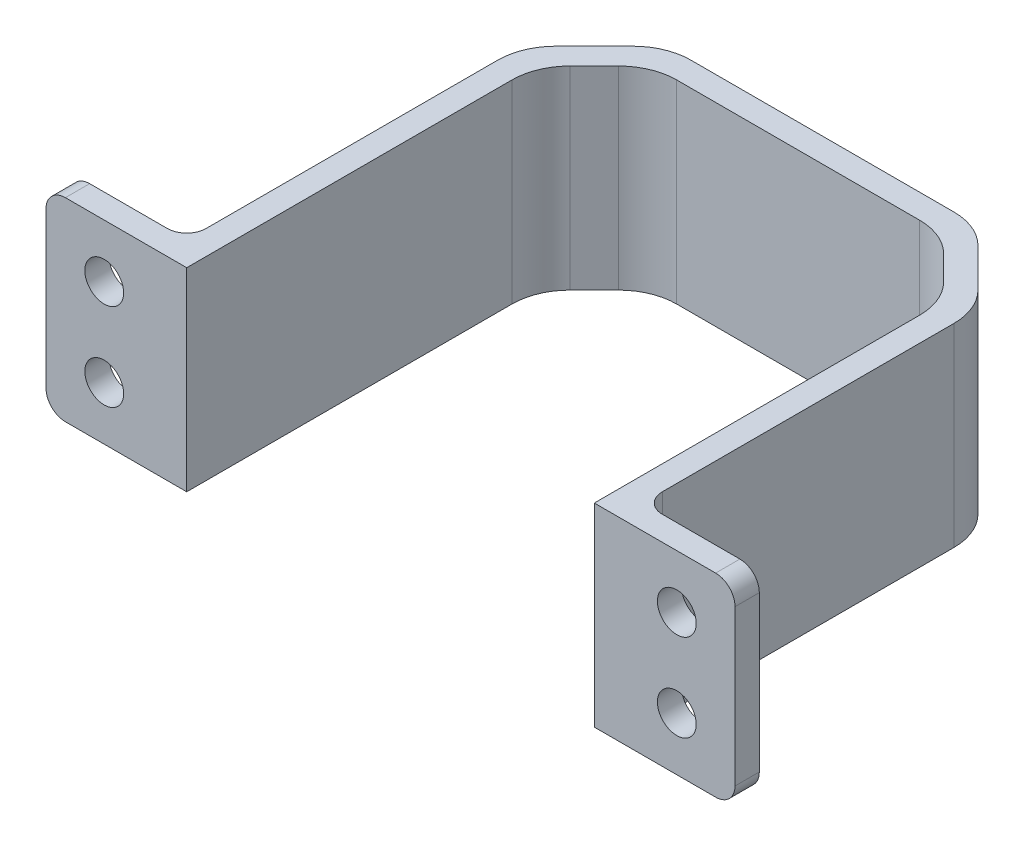
SolidWorks part; units mm, degrees
ref_plane "Front Plane" through (0, 0, 0) normal (0, 0, 1) x (1, 0, 0)
ref_plane "Top Plane" through (0, 0, 0) normal (0, 1, 0) x (1, 0, 0)
ref_plane "Right Plane" through (0, 0, 0) normal (1, 0, 0) x (0, 0, -1)
sketch "Sketch1" plane through (0, 0, 0) normal (0, 1, 0) x (1, 0, 0)
  line L0 (-107.311, 0) -> (118.9665, 0) construction
  line L17 (0, -58.7799) -> (0, 69.8325) construction
  line L18 (-35.5, 0) -> (-21, 0)
  line L19 (-21, 0) -> (-21, 36)
  line L20 (-21, 36) -> (-15, 42)
  line L21 (-15, 42) -> (15, 42)
  line L22 (0, 42) -> (0, 44.5)
  line L23 (16.0355, 44.5) -> (-16.0355, 44.5)
  line L24 (-16.0355, 44.5) -> (-23.5, 37.0355)
  line L25 (-23.5, 37.0355) -> (-23.5, 2.5)
  line L26 (-23.5, 2.5) -> (-35.5, 2.5)
  line L27 (-35.5, 2.5) -> (-35.5, 0)
  line L28 (35.5, 2.5) -> (35.5, 0)
  line L29 (23.5, 2.5) -> (35.5, 2.5)
  line L30 (23.5, 37.0355) -> (23.5, 2.5)
  line L31 (16.0355, 44.5) -> (23.5, 37.0355)
  line L32 (21, 36) -> (15, 42)
  line L33 (21, 0) -> (21, 36)
  line L34 (35.5, 0) -> (21, 0)
  dimension "D1" = 21
  dimension "D2" = 42
  dimension "D3" = 225
  dimension "D4" = 15
  dimension "D5" = 2.5
  dimension "D6" = 2.5
  dimension "D7" = 2.5
  dimension "D8" = 2.5
  dimension "D9" = 12
extrude "Boss-Extrude1" add sketch "Sketch1" along normal blind 20 contours L25 L26 L27 L18 L19 L20 L21 L32 L33 L34 L28 L29 L30 L31 L23 L24
sketch "Sketch2" plane through (0, 0, -2.5) normal (0, 0, -1) x (-1, 0, 0)
  line L0 (35.5, 20) -> (35.5, 0) construction
  line L1 (23.5, 20) -> (35.5, 20) construction
  line L2 (23.5, 0) -> (35.5, 0) construction
  circle A0 centre (29.5, 14.5) radius 2
  circle A1 centre (29.5, 5.5) radius 2
  point P4 (0, 0)
  dimension "D1" = 4
  dimension "D2" = 4
  dimension "D3" = 6
  dimension "D4" = 5.5
  dimension "D5" = 5.5
extrude "Cut-Extrude1" cut sketch "Sketch2" against normal through all
mirror "Mirror1" about plane through (0, 0, 0) normal (1, 0, 0) of "Cut-Extrude1"
fillet "Fillet1" radius 6 4 edges at (-23.5, 10, -37.0355) (-16.0355, 10, -44.5) (23.5, 10, -37.0355) (16.0355, 10, -44.5)
fillet "Fillet2" radius 6 4 edges at (-21, 10, -36) (-15, 10, -42) (21, 10, -36) (15, 10, -42)
fillet "Fillet3" radius 2 2 edges at (-23.5, 10, -2.5) (23.5, 10, -2.5)
fillet "Fillet4" radius 2 4 edges at (-35.5, 0, -1.25) (-35.5, 20, -1.25) (35.5, 20, -1.25) (35.5, 0, -1.25)
